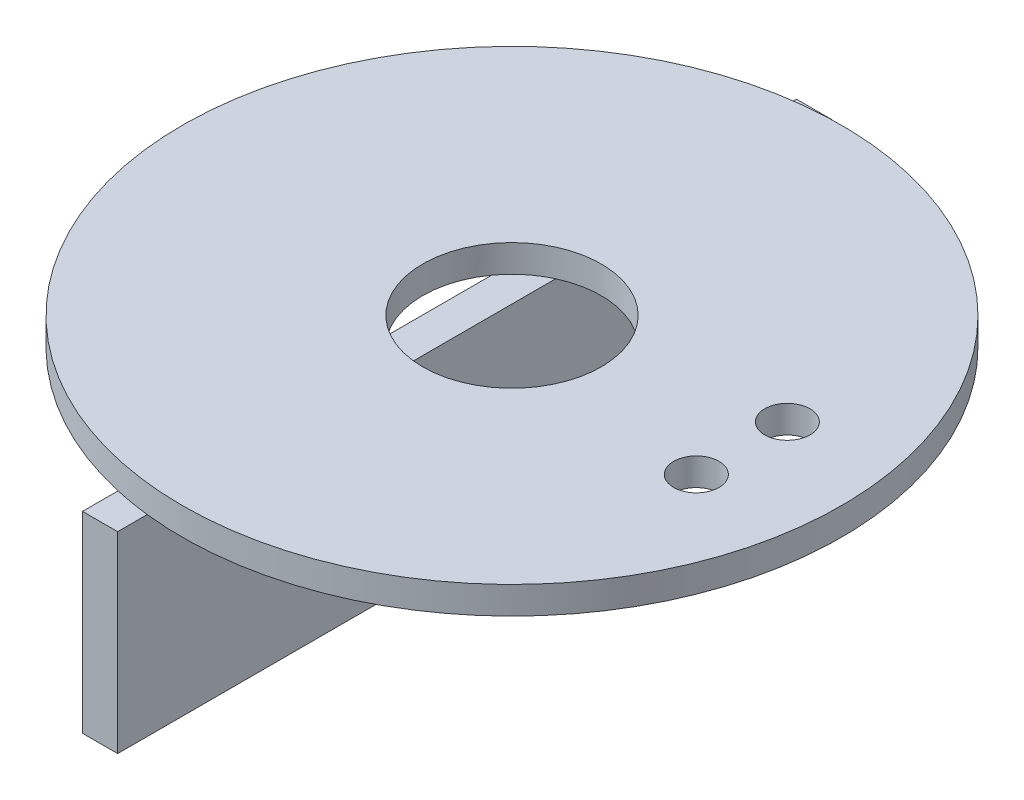
SolidWorks part; units mm, degrees
ref_plane "Front Plane" through (0, 0, 0) normal (0, 0, 1) x (1, 0, 0)
ref_plane "Top Plane" through (0, 0, 0) normal (0, 1, 0) x (1, 0, 0)
ref_plane "Right Plane" through (0, 0, 0) normal (1, 0, 0) x (0, 0, -1)
sketch "Sketch1" plane through (0, 0, 0) normal (0, 1, 0) x (1, 0, 0)
  circle A0 centre (0, 0) radius 24
  dimension "D1" = 48
extrude "Boss-Extrude1" add sketch "Sketch1" along normal blind 2
sketch "Sketch6" plane through (0, 2, 0) normal (0, 1, 0) x (1, 0, 0)
  circle A1 centre (0, 0) radius 6.5
  dimension "D1" = 13
extrude "Cut-Extrude4" cut sketch "Sketch6" against normal blind 2.4
sketch "Sketch11" plane through (0, 2, 0) normal (0, -1, 0) x (1, 0, 0)
  line L0 (16.74, 3.315) -> (16.74, -3.315) construction
  line L1 (0, 0) -> (16.74, 0) construction
  circle A0 centre (16.74, 3.315) radius 1.65
  circle A1 centre (16.74, -3.315) radius 1.65
  point P6 (16.74, 0)
  dimension "D1" = 3.3
  dimension "D2" = 6.63
  dimension "D3" = 16.74
extrude "Cut-Extrude8" cut sketch "Sketch11" along normal through all
sketch "Sketch12" plane through (0, 0, 0) normal (0, 1, 0) x (1, 0, 0)
  line L0 (0, 0) -> (-24, 0) construction
  line L2 (-5.2793, -26) -> (-2.7207, -26)
  line L3 (-5.2793, -26) -> (-5.2793, 26)
  line L4 (-5.2793, 26) -> (-2.7207, 26)
  line L5 (-2.7207, -26) -> (-2.7207, 26)
  line L6 (-5.2793, -26) -> (-2.7207, 26) construction
  line L7 (-5.2793, 26) -> (-2.7207, -26) construction
  circle A0 centre (0, 0) radius 24 construction
  point P6 (-4, 0)
  dimension "D1" = 4
  dimension "D2" = 52
extrude "Boss-Extrude2" add sketch "Sketch12" against normal blind 14
